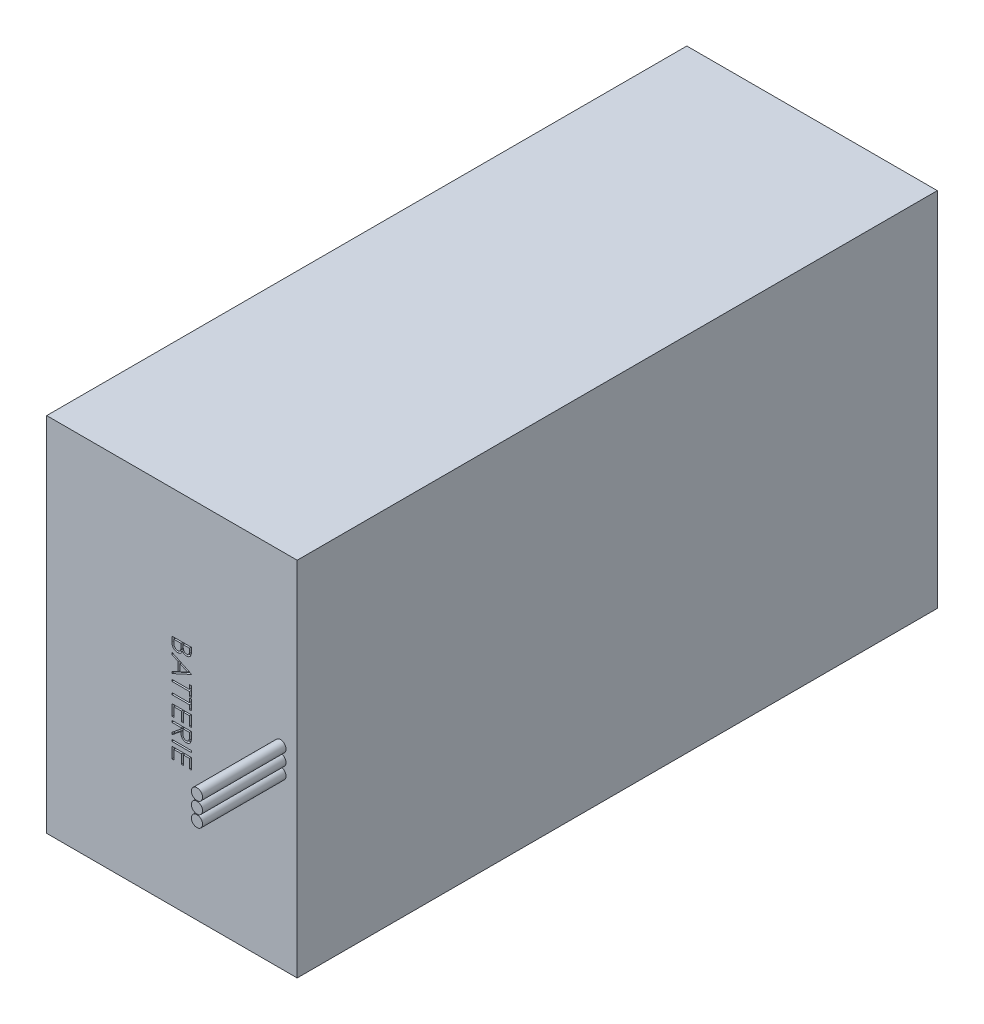
SolidWorks part; units mm, degrees
ref_plane "Plan de face" through (0, 0, 0) normal (0, 0, 1) x (1, 0, 0)
ref_plane "Plan de dessus" through (0, 0, 0) normal (0, 1, 0) x (1, 0, 0)
ref_plane "Plan de droite" through (0, 0, 0) normal (1, 0, 0) x (0, 0, -1)
sketch "Esquisse1" plane through (0, 0, 0) normal (0, 0, 1) x (1, 0, 0)
  line L1 (0, 0) -> (45, 0)
  line L2 (0, 0) -> (0, 65)
  line L3 (0, 65) -> (45, 65)
  line L4 (45, 0) -> (45, 65)
  dimension "D1" = 45
  dimension "D2" = 65
extrude "Boss.-Extru.1" add sketch "Esquisse1" along normal blind 115
sketch "Esquisse2" plane through (0, 0, 115) normal (0, 0, 1) x (1, 0, 0)
  line L1 (45, 65) -> (0, 65) construction
  line L2 (45, 0) -> (45, 65) construction
  circle A0 centre (42, 34.6) radius 1
  circle A1 centre (42, 32.5) radius 1
  circle A2 centre (42, 30.4) radius 1
  dimension "D1" = 2
  dimension "D2" = 2
  dimension "D3" = 2
  dimension "D4" = 2.1
  dimension "D5" = 2.1
  dimension "D6" = 32.5
  dimension "D7" = 3
  dimension "D8" = 3
  dimension "D9" = 3
extrude "Boss.-Extru.2" add sketch "Esquisse2" along normal blind 15
sketch "Esquisse4" plane through (0, 0, 115) normal (0, 0, 1) x (1, 0, 0)
  line L0 (22.5, 65) -> (22.5, 0) construction
  line L1 (45, 65) -> (0, 65) construction
  line L2 (0, 0) -> (45, 0) construction
  text T0 "BATTERIE"
  point P4 (22.5, 0)
extrude "Enlèv. mat.-Extru.2" cut sketch "Esquisse4" against normal blind 0.5
equation "\"D8@Esquisse2\"=\"D7@Esquisse2\""
equation "\"D9@Esquisse2\"=\"D7@Esquisse2\""
